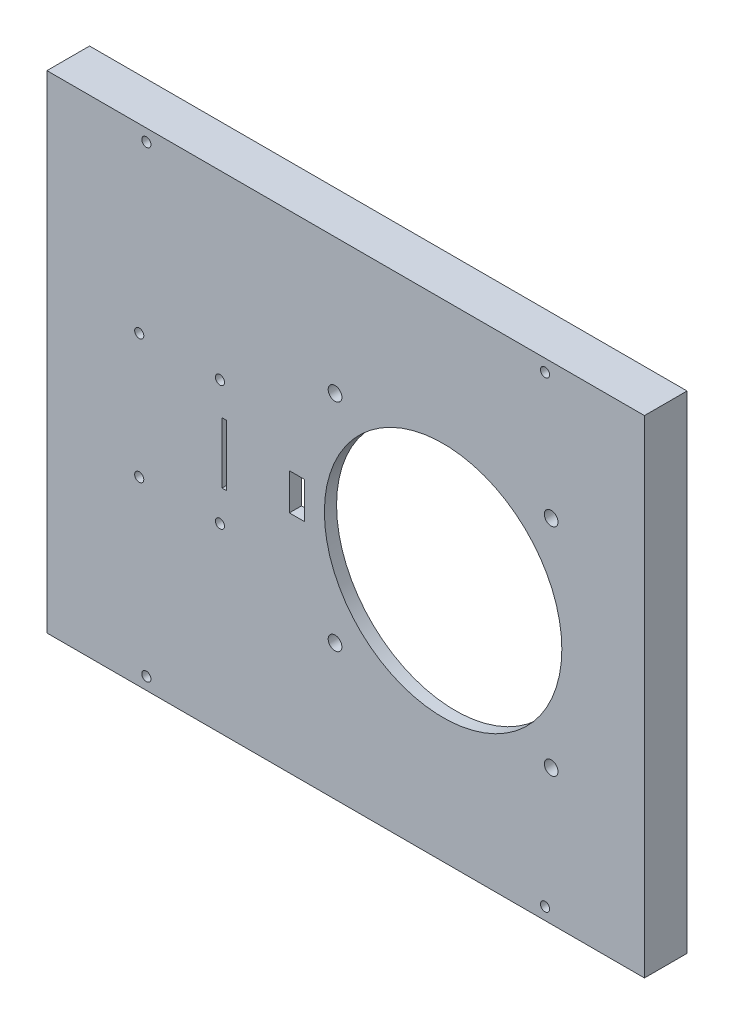
SolidWorks part; units mm, degrees
ref_plane "Piano frontale" through (0, 0, 0) normal (0, 0, 1) x (1, 0, 0)
ref_plane "Piano superiore" through (0, 0, 0) normal (0, 1, 0) x (1, 0, 0)
ref_plane "Piano destro" through (0, 0, 0) normal (1, 0, 0) x (0, 0, -1)
sketch "Schizzo1" plane through (0, 0, 0) normal (0, 0, 1) x (1, 0, 0)
  line L1 (98.1384, -80) -> (-98.1384, -80)
  line L2 (98.1384, -80) -> (98.1384, 80)
  line L3 (98.1384, 80) -> (-98.1384, 80)
  line L4 (-98.1384, -80) -> (-98.1384, 80)
  line L5 (98.1384, -80) -> (-98.1384, 80) construction
  line L6 (98.1384, 80) -> (-98.1384, -80) construction
  line L7 (80, -73) -> (-80, -73)
  line L8 (80, -73) -> (80, 73)
  line L9 (80, 73) -> (-80, 73)
  line L10 (-80, -73) -> (-80, 73)
  line L11 (80, -73) -> (-80, 73) construction
  line L12 (80, 73) -> (-80, -73) construction
  point P0 (0, 0)
  point P6 (0, 0)
  dimension "D1" = 160
  dimension "D2" = 196.2767
  dimension "D3" = 146
  dimension "D4" = 160
extrude "Estrusione-Estrusione1" add sketch "Schizzo1" along normal blind 10
sketch "Schizzo2" plane through (0, 0, 10) normal (0, 0, 1) x (1, 0, 0)
  line L1 (98.1384, -80) -> (-98.1384, -80)
  line L2 (98.1384, -80) -> (98.1384, 80)
  line L3 (98.1384, 80) -> (-98.1384, 80)
  line L4 (-98.1384, -80) -> (-98.1384, 80)
  line L5 (98.1384, -80) -> (-98.1384, 80) construction
  line L6 (98.1384, 80) -> (-98.1384, -80) construction
  point P0 (0, 0)
extrude "Estrusione-Estrusione2" add sketch "Schizzo2" along normal blind 4
sketch "Schizzo3" plane through (0, 0, 0) normal (0, 0, -1) x (-1, 0, 0)
  line L0 (80, 73) -> (-80, 73) construction
  line L1 (0, 73) -> (0, 80) construction
  line L2 (-98.1384, 80) -> (98.1384, 80) construction
  line L3 (65.4833, 73) -> (65.4833, 76) construction
  line L4 (0, 0) -> (67.2528, 0) construction
  circle A0 centre (65.4833, 76) radius 1.5
  circle A1 centre (-65.4833, 76) radius 1.5
  circle A2 centre (-65.4833, -76) radius 1.5
  circle A3 centre (65.4833, -76) radius 1.5
  dimension "D3" = 3
  dimension "D1" = 3
  dimension "D2" = 65.4833
extrude "Taglio-Estrusione1" cut sketch "Schizzo3" against normal blind 93
sketch "Schizzo4" plane through (0, 0, 10) normal (0, 0, -1) x (-1, 0, 0)
  line L0 (0, 0) -> (-32, 0) construction
  line L1 (-32, 0) -> (-32, 39) construction
  line L2 (-32, 0) -> (3.5, 35.5) construction
  line L3 (-32, 0) -> (16, 0) construction
  line L4 (18.5, -6) -> (13.5, -6)
  line L5 (18.5, -6) -> (18.5, 6)
  line L6 (18.5, 6) -> (13.5, 6)
  line L7 (13.5, -6) -> (13.5, 6)
  line L8 (18.5, -6) -> (13.5, 6) construction
  line L9 (18.5, 6) -> (13.5, -6) construction
  line L10 (39.1226, 0) -> (80.8774, 0) construction
  line L11 (39.1226, 23.8052) -> (70, 23.8052) construction
  line L12 (70, 23.8052) -> (70, -23.8052) construction
  line L13 (41.2991, 20.4492) -> (41.2991, -20.4492) construction
  line L14 (39.1226, 23.8052) -> (70, -23.8052) construction
  line L15 (70, 23.8052) -> (39.1226, -23.8052) construction
  line L16 (39.1226, 10) -> (40.6226, 10)
  line L17 (40.6226, 10) -> (40.6226, -10)
  line L18 (40.6226, -10) -> (39.1226, -10)
  line L19 (39.1226, -10) -> (39.1226, 10)
  line L20 (80, 73) -> (80, -73) construction
  line L21 (-80, 0) -> (80, 0) construction
  line L22 (-80, -73) -> (-80, 73) construction
  line L23 (41.2991, 20.4492) -> (41.2991, -20.4492) construction
  line L24 (67.8235, 20.4492) -> (67.8235, -20.4492) construction
  line L25 (41.2991, 0) -> (62.6698, 0) construction
  circle A0 centre (-32, 0) radius 39
  circle A1 centre (3.5, 35.5) radius 2.25
  circle A2 centre (3.5, -35.5) radius 2.25
  circle A3 centre (-67.5, 35.5) radius 2.25
  circle A4 centre (-67.5, -35.5) radius 2.25
  circle A5 centre (41.2991, 20.4492) radius 1.5
  circle A6 centre (41.2991, -20.4492) radius 1.5
  circle A7 centre (67.8235, -20.4492) radius 1.5
  circle A8 centre (67.8235, 20.4492) radius 1.5
  point P37 (60, 0)
  dimension "D3" = 4.5
  dimension "D9" = 78
  dimension "D10" = 0
  dimension "D12" = 3
  dimension "D13" = 3
  dimension "D14" = 3
  dimension "D15" = 3
  dimension "D1" = 45
  dimension "D2" = 0
  dimension "D4" = 12
  dimension "D5" = 5
  dimension "D6" = 0
  dimension "D7" = 32
  dimension "D8" = 48
  dimension "D11" = 30.8774
  dimension "D16" = 4
  dimension "D17" = 4
  dimension "D18" = 4
  dimension "D19" = 4
  dimension "D20" = 1.5
  dimension "D22" = 20
  dimension "D23" = 20
  dimension "D24" = 10
  dimension "D25" = 0
  dimension "D26" = 56.7465
extrude "Taglio-Estrusione2" cut sketch "Schizzo4" against normal blind 90
